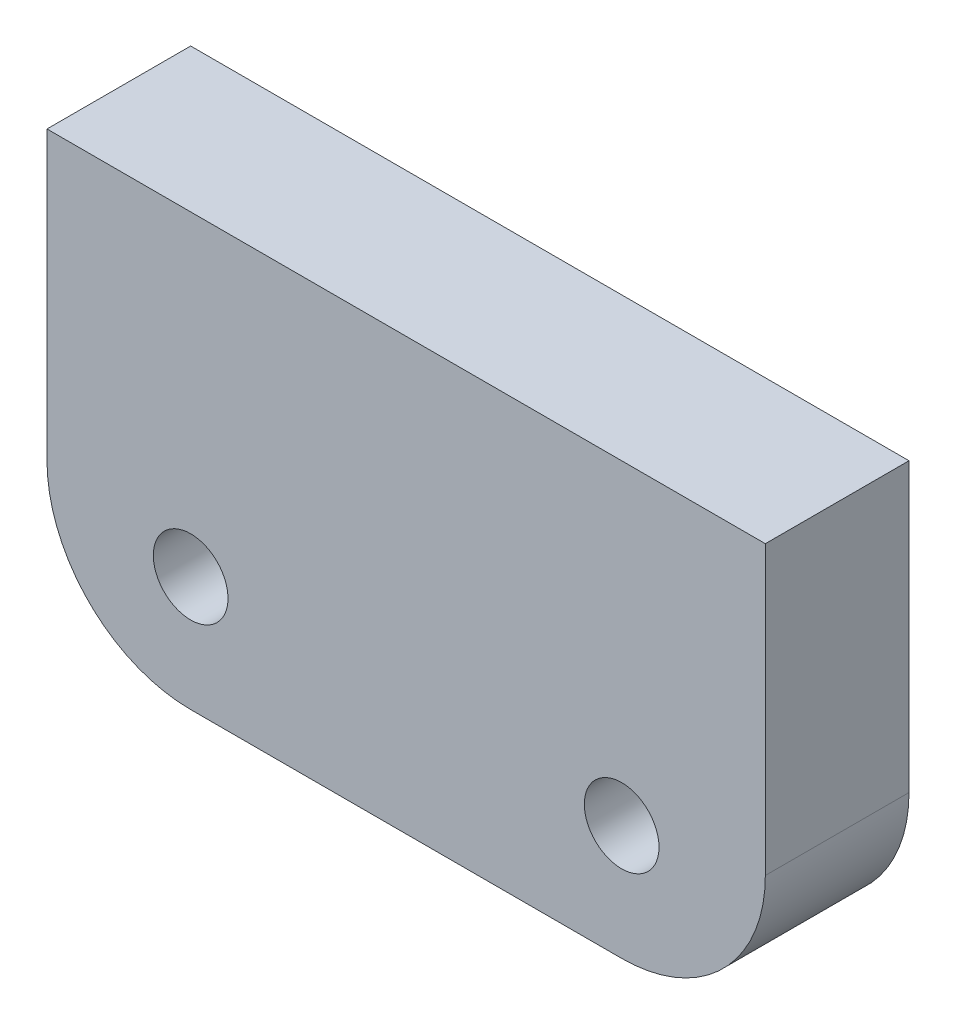
SolidWorks part; units mm, degrees
ref_plane "Front Plane" through (0, 0, 0) normal (0, 0, 1) x (1, 0, 0)
ref_plane "Top Plane" through (0, 0, 0) normal (0, 1, 0) x (1, 0, 0)
ref_plane "Right Plane" through (0, 0, 0) normal (1, 0, 0) x (0, 0, -1)
sketch "Sketch1" plane through (0, 0, 0) normal (0, 0, 1) x (1, 0, 0)
  line L0 (-46, 449.9497) -> (46, 449.9497) construction
  line L1 (-25, 449.9497) -> (25, 449.9497)
  line L2 (-25, 449.9497) -> (-25, 419.9497)
  line L3 (-25, 419.9497) -> (25, 419.9497)
  line L4 (25, 449.9497) -> (25, 419.9497)
  line L5 (0, -167.241) -> (0, 464.2536) construction
  line L6 (-19.9686, 464.2536) -> (19.9686, 464.2536) construction
  spline S0 degree 1 poles (0, 10) (0, -167.241) knots 0 0 0.984672 0.984672 construction
  dimension "D1" = 50
  dimension "D2" = 25
  dimension "D3" = 30
extrude "Boss-Extrude1" add sketch "Sketch1" along normal blind 10
sketch "Sketch2" plane through (0, 0, 0) normal (0, 0, -1) x (-1, 0, 0)
  line L0 (0, 419.9497) -> (0, 449.9497) construction
  line L1 (25, 419.9497) -> (-25, 419.9497) construction
  line L2 (-25, 449.9497) -> (25, 449.9497) construction
  line L3 (11, 430.2591) -> (15, 432.5685)
  line L4 (11, 425.6403) -> (11, 430.2591)
  line L5 (-15, 432.5685) -> (-19, 430.2591)
  line L6 (-19, 430.2591) -> (-19, 425.6403)
  line L7 (-19, 425.6403) -> (-15, 423.3309)
  line L8 (-15, 423.3309) -> (-11, 425.6403)
  line L9 (-11, 425.6403) -> (-11, 430.2591)
  line L10 (-11, 430.2591) -> (-15, 432.5685)
  line L11 (15, 423.3309) -> (11, 425.6403)
  line L12 (19, 425.6403) -> (15, 423.3309)
  line L13 (19, 430.2591) -> (19, 425.6403)
  line L14 (15, 432.5685) -> (19, 430.2591)
  circle A0 centre (-15, 427.9497) radius 4 construction
  circle A1 centre (15, 427.9497) radius 4 construction
  dimension "D3" = 8
extrude "Cut-Extrude1" cut sketch "Sketch2" against normal blind 5
sketch "Sketch3" plane through (0, 0, 5) normal (0, 0, -1) x (-1, 0, 0)
  line L0 (0, 419.9497) -> (0, 449.9497) construction
  line L1 (25, 419.9497) -> (-25, 419.9497) construction
  line L2 (-25, 449.9497) -> (25, 449.9497) construction
  line L3 (15, 423.3309) -> (15, 427.9497) construction
  line L4 (15, 427.9497) -> (11, 427.9497) construction
  line L5 (11, 430.2591) -> (11, 425.6403) construction
  line L6 (-15, 427.9497) -> (-11, 427.9497) construction
  line L7 (-15, 423.3309) -> (-15, 427.9497) construction
  circle A0 centre (15, 427.9497) radius 2.6
  circle A1 centre (-15, 427.9497) radius 2.6
extrude "Cut-Extrude2" cut sketch "Sketch3" against normal through all
fillet "Fillet1" radius 10 2 edges at (-25, 419.9497, 5) (25, 419.9497, 5)
